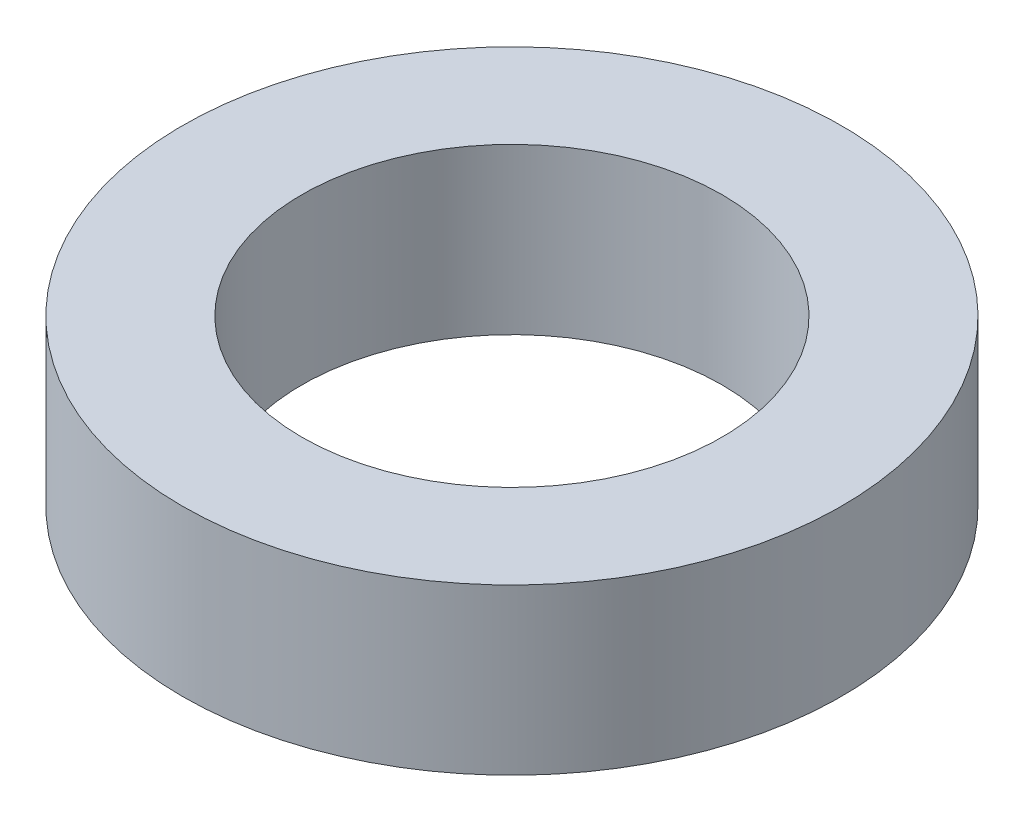
SolidWorks part; units mm, degrees
ref_plane "Front" through (0, 0, 0) normal (0, 0, 1) x (1, 0, 0)
ref_plane "Top" through (0, 0, 0) normal (0, 1, 0) x (1, 0, 0)
ref_plane "Right" through (0, 0, 0) normal (1, 0, 0) x (0, 0, -1)
sketch "Sketch1" plane through (0, 0, 0) normal (0, 1, 0) x (1, 0, 0)
  circle A0 centre (0, 0) radius 4
  circle A1 centre (0, 0) radius 2.55
  dimension "D1" = 8
  dimension "D2" = 5.1
extrude "Boss-Extrude1" add sketch "Sketch1" along normal blind 2
